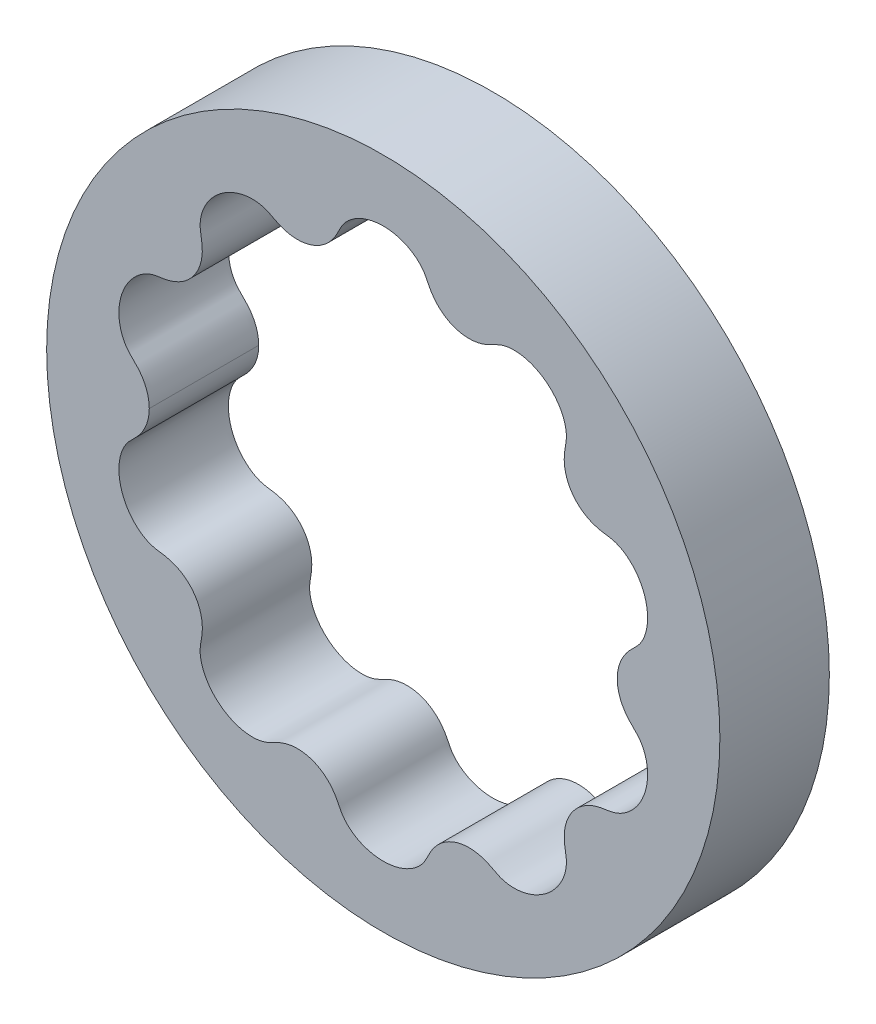
SolidWorks part; units mm, degrees
ref_plane "Plan de face" through (0, 0, 0) normal (0, 0, 1) x (1, 0, 0)
ref_plane "Plan de dessus" through (0, 0, 0) normal (0, 1, 0) x (1, 0, 0)
ref_plane "Plan de droite" through (0, 0, 0) normal (1, 0, 0) x (0, 0, -1)
sketch "Esquisse1" plane through (0, 0, 0) normal (0, 0, 1) x (1, 0, 0)
  line L0 (-1000, 0) -> (49000, 0) construction
  circle A1 centre (0, 0) radius 12.3
  spline S0 degree 4 poles (9.65, 2.2938) (9.6438, 2.2276) (9.6248, 2.0962) (9.5801, 1.9114) (9.4854, 1.6842) (9.3662, 1.4918) (9.2274, 1.3412) (9.0846, 1.2104) (8.9589, 1.0771) (8.839, 0.9248) (8.7465, 0.7744) (8.6778, 0.6314) (8.6289, 0.4989) (8.5973, 0.3904) (8.5734, 0.282) (8.5574, 0.1693) (8.55, 0.0513) (8.5493, -0.0214) (8.5534, -0.1079) (8.5608, -0.19) (8.5775, -0.3076) (8.6125, -0.4561) (8.6727, -0.6284) (8.7656, -0.8089) (8.8701, -0.9663) (8.9792, -1.0997) (9.092, -1.2163) (9.2028, -1.3198) (9.3015, -1.4211) (9.3828, -1.524) (9.4698, -1.6619) (9.5525, -1.8386) (9.6351, -2.1061) (9.6765, -2.4694) (9.6393, -2.8813) (9.498, -3.3193) (9.2932, -3.6687) (9.0622, -3.9301) (8.8333, -4.1123) (8.6283, -4.2299) (8.4212, -4.3081) (8.2196, -4.3424) (7.9802, -4.3715) (7.6899, -4.439) (7.3558, -4.5875) (7.0211, -4.8585) (6.7965, -5.1796) (6.6738, -5.4888) (6.6133, -5.7918) (6.6044, -6.0362) (6.6285, -6.269) (6.6743, -6.4977) (6.6997, -6.6953) (6.687, -6.9148) (6.6356, -7.1483) (6.5291, -7.4227) (6.3478, -7.7216) (6.0798, -8.0168) (5.7169, -8.2767) (5.35, -8.4347) (5.0073, -8.5082) (4.7111, -8.5186) (4.4712, -8.4898) (4.2096, -8.4126) (3.9532, -8.2569) (3.6301, -8.1121) (3.2266, -8.0331) (2.7973, -8.0626) (2.4273, -8.198) (2.1494, -8.3815) (1.9589, -8.5637) (1.8333, -8.7178) (1.7306, -8.8762) (1.6466, -9.0341) (1.5684, -9.2056) (1.4685, -9.3775) (1.3274, -9.5427) (1.1497, -9.6955) (0.9048, -9.8496) (0.5863, -9.9809) (0.2026, -10.0592) (-0.2348, -10.0558) (-0.6142, -9.9721) (-0.9251, -9.8387) (-1.1632, -9.6849) (-1.3355, -9.5343) (-1.4734, -9.3706) (-1.5716, -9.1988) (-1.6495, -9.0281) (-1.7336, -8.8711) (-1.8364, -8.7136) (-1.9619, -8.5606) (-2.1517, -8.3798) (-2.4288, -8.1974) (-2.7979, -8.0626) (-3.2266, -8.0331) (-3.6301, -8.1121) (-3.9532, -8.2569) (-4.2096, -8.4126) (-4.4712, -8.4898) (-4.7111, -8.5186) (-5.0073, -8.5082) (-5.35, -8.4347) (-5.7169, -8.2767) (-6.0798, -8.0168) (-6.3478, -7.7216) (-6.5291, -7.4227) (-6.6356, -7.1483) (-6.687, -6.9148) (-6.6997, -6.6953) (-6.6743, -6.4977) (-6.6285, -6.269) (-6.6044, -6.0362) (-6.6133, -5.7918) (-6.6738, -5.4888) (-6.7965, -5.1796) (-7.0211, -4.8585) (-7.3558, -4.5875) (-7.6899, -4.439) (-7.9802, -4.3715) (-8.2196, -4.3424) (-8.4212, -4.3081) (-8.6283, -4.2299) (-8.8333, -4.1123) (-9.0622, -3.9301) (-9.2932, -3.6687) (-9.498, -3.3192) (-9.6393, -2.8813) (-9.6823, -2.4045) (-9.6198, -2.009) (-9.5043, -1.7166) (-9.3828, -1.524) (-9.3015, -1.4211) (-9.2028, -1.3198) (-9.092, -1.2162) (-8.9792, -1.0998) (-8.8701, -0.9661) (-8.7656, -0.8092) (-8.6861, -0.6539) (-8.6288, -0.5032) (-8.5927, -0.3716) (-8.5733, -0.278) (-8.5608, -0.19) (-8.5534, -0.1079) (-8.5493, -0.0214) (-8.55, 0.0513) (-8.5574, 0.1693) (-8.5734, 0.282) (-8.5973, 0.3904) (-8.6289, 0.4989) (-8.6778, 0.6314) (-8.7465, 0.7744) (-8.839, 0.9248) (-8.9589, 1.0771) (-9.0846, 1.2104) (-9.2274, 1.3412) (-9.3662, 1.4918) (-9.4854, 1.6842) (-9.5801, 1.9114) (-9.6248, 2.0962) (-9.6438, 2.2276) (-9.65, 2.2938) knots 0 0 0 0 0 0.006705 0.013411 0.019098 0.024786 0.029406 0.034025 0.038645 0.043265 0.048956 0.051802 0.054648 0.057492 0.060337 0.063182 0.066026 0.067956 0.069886 0.071816 0.073746 0.079675 0.085604 0.089956 0.094308 0.09866 0.103012 0.106316 0.109621 0.112926 0.116231 0.122746 0.129261 0.141085 0.152909 0.164139 0.175368 0.181654 0.18794 0.193553 0.199166 0.203852 0.208537 0.217908 0.229156 0.240403 0.251447 0.256969 0.262492 0.271512 0.276022 0.280532 0.286049 0.291565 0.298085 0.304606 0.31564 0.326674 0.33802 0.349366 0.355624 0.361882 0.367803 0.373725 0.382888 0.392051 0.403412 0.414778 0.425786 0.431295 0.436803 0.441312 0.445821 0.45033 0.454839 0.460338 0.465837 0.472137 0.478437 0.489438 0.500439 0.511373 0.522307 0.528364 0.534421 0.539887 0.545352 0.549845 0.554338 0.558831 0.563324 0.568801 0.574278 0.585222 0.596588 0.607949 0.617112 0.626275 0.632197 0.638118 0.644376 0.650634 0.66198 0.673326 0.68436 0.695394 0.701915 0.708435 0.713951 0.719468 0.723978 0.728488 0.737508 0.743031 0.748553 0.759597 0.770844 0.782092 0.791463 0.796148 0.800834 0.806447 0.81206 0.818346 0.824632 0.835861 0.847091 0.858915 0.870739 0.883769 0.887074 0.890379 0.893684 0.896988 0.90134 0.905692 0.910044 0.914396 0.920325 0.923289 0.926254 0.928184 0.930114 0.932044 0.933974 0.936818 0.939663 0.942508 0.945352 0.948198 0.951044 0.956735 0.961355 0.965975 0.970594 0.975214 0.980902 0.986589 0.993295 1 1 1 1 1 construction
  spline S1 degree 4 poles (8.55, 0) (8.55, -0.0166) (8.5506, -0.0499) (8.5534, -0.1079) (8.5608, -0.19) (8.5775, -0.3076) (8.6125, -0.4561) (8.6727, -0.6284) (8.7656, -0.8089) (8.8701, -0.9663) (8.9792, -1.0997) (9.092, -1.2163) (9.2028, -1.3198) (9.3015, -1.4211) (9.3828, -1.524) (9.4698, -1.6619) (9.5525, -1.8386) (9.6351, -2.1061) (9.6765, -2.4694) (9.6393, -2.8813) (9.498, -3.3193) (9.2932, -3.6687) (9.0622, -3.9301) (8.8333, -4.1123) (8.6283, -4.2299) (8.4212, -4.3081) (8.2196, -4.3424) (7.9802, -4.3715) (7.6899, -4.439) (7.3558, -4.5875) (7.0211, -4.8585) (6.7965, -5.1796) (6.6738, -5.4888) (6.6133, -5.7918) (6.6044, -6.0362) (6.6285, -6.269) (6.6743, -6.4977) (6.6997, -6.6953) (6.687, -6.9148) (6.6356, -7.1483) (6.5291, -7.4227) (6.3478, -7.7216) (6.0798, -8.0168) (5.7169, -8.2767) (5.35, -8.4347) (5.0073, -8.5082) (4.7111, -8.5186) (4.4712, -8.4898) (4.2096, -8.4126) (3.9532, -8.2569) (3.6301, -8.1121) (3.2266, -8.0331) (2.7973, -8.0626) (2.4273, -8.198) (2.1494, -8.3815) (1.9589, -8.5637) (1.8333, -8.7178) (1.7306, -8.8762) (1.6466, -9.0341) (1.5684, -9.2056) (1.4685, -9.3775) (1.3274, -9.5427) (1.1497, -9.6955) (0.9048, -9.8496) (0.5863, -9.9809) (0.2026, -10.0592) (-0.2348, -10.0558) (-0.6142, -9.9721) (-0.9251, -9.8387) (-1.1632, -9.6849) (-1.3355, -9.5343) (-1.4734, -9.3706) (-1.5716, -9.1988) (-1.6495, -9.0281) (-1.7336, -8.8711) (-1.8364, -8.7136) (-1.9619, -8.5606) (-2.1517, -8.3798) (-2.4288, -8.1974) (-2.7979, -8.0626) (-3.2266, -8.0331) (-3.6301, -8.1121) (-3.9532, -8.2569) (-4.2096, -8.4126) (-4.4712, -8.4898) (-4.7111, -8.5186) (-5.0073, -8.5082) (-5.35, -8.4347) (-5.7169, -8.2767) (-6.0798, -8.0168) (-6.3478, -7.7216) (-6.5291, -7.4227) (-6.6356, -7.1483) (-6.687, -6.9148) (-6.6997, -6.6953) (-6.6743, -6.4977) (-6.6285, -6.269) (-6.6044, -6.0362) (-6.6133, -5.7918) (-6.6738, -5.4888) (-6.7965, -5.1796) (-7.0211, -4.8585) (-7.3558, -4.5875) (-7.6899, -4.439) (-7.9802, -4.3715) (-8.2196, -4.3424) (-8.4212, -4.3081) (-8.6283, -4.2299) (-8.8333, -4.1123) (-9.0622, -3.9301) (-9.2932, -3.6687) (-9.498, -3.3192) (-9.6393, -2.8813) (-9.6823, -2.4045) (-9.6198, -2.009) (-9.5043, -1.7166) (-9.3828, -1.524) (-9.3015, -1.4211) (-9.2028, -1.3198) (-9.092, -1.2162) (-8.9792, -1.0998) (-8.8701, -0.9661) (-8.7656, -0.8092) (-8.6861, -0.6539) (-8.6288, -0.5032) (-8.5927, -0.3716) (-8.5733, -0.278) (-8.5608, -0.19) (-8.5534, -0.1079) (-8.5506, -0.0499) (-8.55, -0.0166) (-8.55, 0) knots 0.066026 0.066026 0.066026 0.066026 0.066026 0.067956 0.069886 0.071816 0.073746 0.079675 0.085604 0.089956 0.094308 0.09866 0.103012 0.106316 0.109621 0.112926 0.116231 0.122746 0.129261 0.141085 0.152909 0.164139 0.175368 0.181654 0.18794 0.193553 0.199166 0.203852 0.208537 0.217908 0.229156 0.240403 0.251447 0.256969 0.262492 0.271512 0.276022 0.280532 0.286049 0.291565 0.298085 0.304606 0.31564 0.326674 0.33802 0.349366 0.355624 0.361882 0.367803 0.373725 0.382888 0.392051 0.403412 0.414778 0.425786 0.431295 0.436803 0.441312 0.445821 0.45033 0.454839 0.460338 0.465837 0.472137 0.478437 0.489438 0.500439 0.511373 0.522307 0.528364 0.534421 0.539887 0.545352 0.549845 0.554338 0.558831 0.563324 0.568801 0.574278 0.585222 0.596588 0.607949 0.617112 0.626275 0.632197 0.638118 0.644376 0.650634 0.66198 0.673326 0.68436 0.695394 0.701915 0.708435 0.713951 0.719468 0.723978 0.728488 0.737508 0.743031 0.748553 0.759597 0.770844 0.782092 0.791463 0.796148 0.800834 0.806447 0.81206 0.818346 0.824632 0.835861 0.847091 0.858915 0.870739 0.883769 0.887074 0.890379 0.893684 0.896988 0.90134 0.905692 0.910044 0.914396 0.920325 0.923289 0.926254 0.928184 0.930114 0.932044 0.933974 0.933974 0.933974 0.933974 0.933974
  spline S2 degree 4 poles (8.55, 0) (8.55, 0.0166) (8.5506, 0.0499) (8.5534, 0.1079) (8.5608, 0.19) (8.5775, 0.3076) (8.6125, 0.4561) (8.6727, 0.6284) (8.7656, 0.8089) (8.8701, 0.9663) (8.9792, 1.0997) (9.092, 1.2163) (9.2028, 1.3198) (9.3015, 1.4211) (9.3828, 1.524) (9.4698, 1.6619) (9.5525, 1.8386) (9.6351, 2.1061) (9.6765, 2.4694) (9.6393, 2.8813) (9.498, 3.3193) (9.2932, 3.6687) (9.0622, 3.9301) (8.8333, 4.1123) (8.6283, 4.2299) (8.4212, 4.3081) (8.2196, 4.3424) (7.9802, 4.3715) (7.6899, 4.439) (7.3558, 4.5875) (7.0211, 4.8585) (6.7965, 5.1796) (6.6738, 5.4888) (6.6133, 5.7918) (6.6044, 6.0362) (6.6285, 6.269) (6.6743, 6.4977) (6.6997, 6.6953) (6.687, 6.9148) (6.6356, 7.1483) (6.5291, 7.4227) (6.3478, 7.7216) (6.0798, 8.0168) (5.7169, 8.2767) (5.35, 8.4347) (5.0073, 8.5082) (4.7111, 8.5186) (4.4712, 8.4898) (4.2096, 8.4126) (3.9532, 8.2569) (3.6301, 8.1121) (3.2266, 8.0331) (2.7973, 8.0626) (2.4273, 8.198) (2.1494, 8.3815) (1.9589, 8.5637) (1.8333, 8.7178) (1.7306, 8.8762) (1.6466, 9.0341) (1.5684, 9.2056) (1.4685, 9.3775) (1.3274, 9.5427) (1.1497, 9.6955) (0.9048, 9.8496) (0.5863, 9.9809) (0.2026, 10.0592) (-0.2348, 10.0558) (-0.6142, 9.9721) (-0.9251, 9.8387) (-1.1632, 9.6849) (-1.3355, 9.5343) (-1.4734, 9.3706) (-1.5716, 9.1988) (-1.6495, 9.0281) (-1.7336, 8.8711) (-1.8364, 8.7136) (-1.9619, 8.5606) (-2.1517, 8.3798) (-2.4288, 8.1974) (-2.7979, 8.0626) (-3.2266, 8.0331) (-3.6301, 8.1121) (-3.9532, 8.2569) (-4.2096, 8.4126) (-4.4712, 8.4898) (-4.7111, 8.5186) (-5.0073, 8.5082) (-5.35, 8.4347) (-5.7169, 8.2767) (-6.0798, 8.0168) (-6.3478, 7.7216) (-6.5291, 7.4227) (-6.6356, 7.1483) (-6.687, 6.9148) (-6.6997, 6.6953) (-6.6743, 6.4977) (-6.6285, 6.269) (-6.6044, 6.0362) (-6.6133, 5.7918) (-6.6738, 5.4888) (-6.7965, 5.1796) (-7.0211, 4.8585) (-7.3558, 4.5875) (-7.6899, 4.439) (-7.9802, 4.3715) (-8.2196, 4.3424) (-8.4212, 4.3081) (-8.6283, 4.2299) (-8.8333, 4.1123) (-9.0622, 3.9301) (-9.2932, 3.6687) (-9.498, 3.3192) (-9.6393, 2.8813) (-9.6823, 2.4045) (-9.6198, 2.009) (-9.5043, 1.7166) (-9.3828, 1.524) (-9.3015, 1.4211) (-9.2028, 1.3198) (-9.092, 1.2162) (-8.9792, 1.0998) (-8.8701, 0.9661) (-8.7656, 0.8092) (-8.6861, 0.6539) (-8.6288, 0.5032) (-8.5927, 0.3716) (-8.5733, 0.278) (-8.5608, 0.19) (-8.5534, 0.1079) (-8.5506, 0.0499) (-8.55, 0.0166) (-8.55, 0) knots 0.066026 0.066026 0.066026 0.066026 0.066026 0.067956 0.069886 0.071816 0.073746 0.079675 0.085604 0.089956 0.094308 0.09866 0.103012 0.106316 0.109621 0.112926 0.116231 0.122746 0.129261 0.141085 0.152909 0.164139 0.175368 0.181654 0.18794 0.193553 0.199166 0.203852 0.208537 0.217908 0.229156 0.240403 0.251447 0.256969 0.262492 0.271512 0.276022 0.280532 0.286049 0.291565 0.298085 0.304606 0.31564 0.326674 0.33802 0.349366 0.355624 0.361882 0.367803 0.373725 0.382888 0.392051 0.403412 0.414778 0.425786 0.431295 0.436803 0.441312 0.445821 0.45033 0.454839 0.460338 0.465837 0.472137 0.478437 0.489438 0.500439 0.511373 0.522307 0.528364 0.534421 0.539887 0.545352 0.549845 0.554338 0.558831 0.563324 0.568801 0.574278 0.585222 0.596588 0.607949 0.617112 0.626275 0.632197 0.638118 0.644376 0.650634 0.66198 0.673326 0.68436 0.695394 0.701915 0.708435 0.713951 0.719468 0.723978 0.728488 0.737508 0.743031 0.748553 0.759597 0.770844 0.782092 0.791463 0.796148 0.800834 0.806447 0.81206 0.818346 0.824632 0.835861 0.847091 0.858915 0.870739 0.883769 0.887074 0.890379 0.893684 0.896988 0.90134 0.905692 0.910044 0.914396 0.920325 0.923289 0.926254 0.928184 0.930114 0.932044 0.933974 0.933974 0.933974 0.933974 0.933974
  dimension "D1" = 24.6
extrude "Boss.-Extru.4" add sketch "Esquisse1" along normal blind 4
equation "\"R\" = 10.8'Radius of the rotor"
equation "\"E\"= 0.75'Eccentricity from input shaft to center of rotor"
equation "\"Rr\"= 1.5'Roller radius"
equation "\"N\" = 11'Amount of rollers"
equation "\"D1@Esquisse1\"=\"R\"*2+3"
